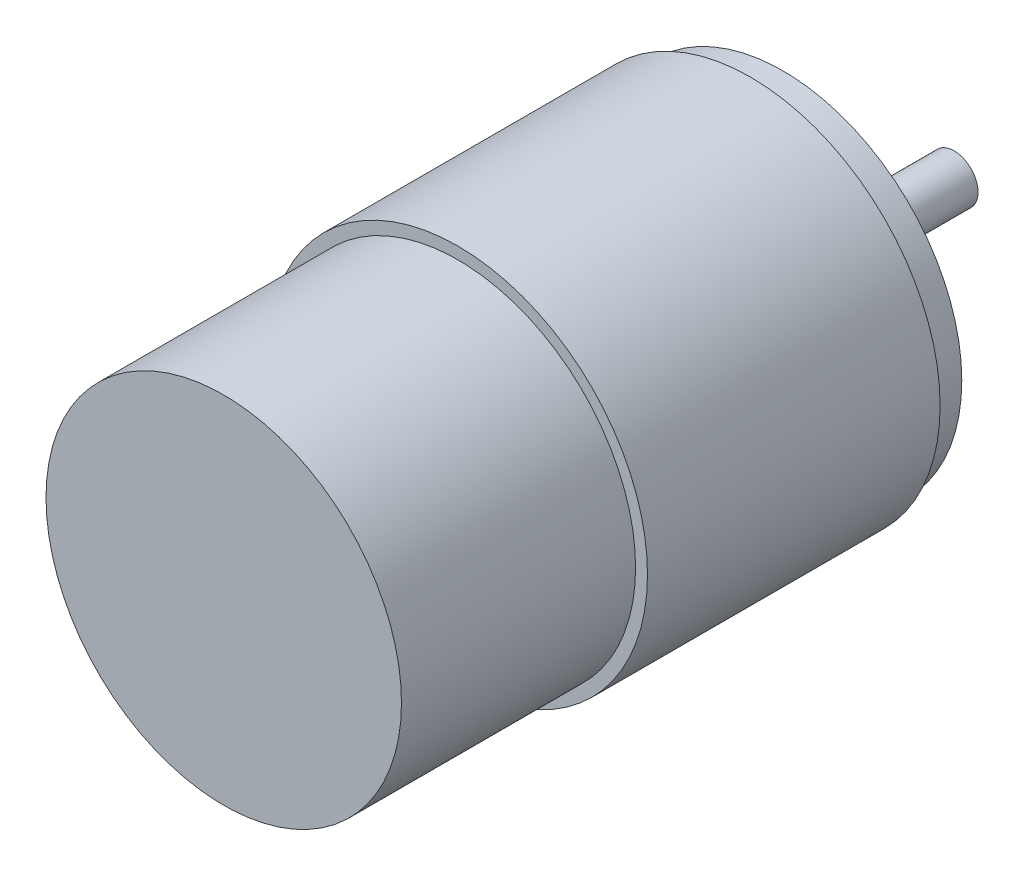
SolidWorks part; units mm, degrees
ref_plane "Front Plane" through (0, 0, 0) normal (0, 0, 1) x (1, 0, 0)
ref_plane "Top Plane" through (0, 0, 0) normal (0, 1, 0) x (1, 0, 0)
ref_plane "Right Plane" through (0, 0, 0) normal (1, 0, 0) x (0, 0, -1)
sketch "Sketch3" plane through (0, 0, 0) normal (0, 0, 1) x (1, 0, 0)
  circle A0 centre (0, 0) radius 20.955
  dimension "D1" = 41.91
extrude "Boss-Extrude3" add sketch "Sketch3" along normal blind 3.81
sketch "Sketch4" plane through (0, 0, 3.81) normal (0, 0, 1) x (1, 0, 0)
  circle A0 centre (0, 0) radius 22.225
  dimension "D1" = 44.45
extrude "Boss-Extrude4" add sketch "Sketch4" along normal blind 34.29
sketch "Sketch5" plane through (0, 0, 38.1) normal (0, 0, 1) x (1, 0, 0)
  circle A0 centre (0, 0) radius 20.828
  dimension "D1" = 41.656
extrude "Boss-Extrude5" add sketch "Sketch5" along normal blind 27.432
sketch "Sketch6" plane through (0, 0, 0) normal (0, 0, -1) x (-1, 0, 0)
  circle A0 centre (0, 0) radius 8.636
  dimension "D1" = 17.272
extrude "Boss-Extrude6" add sketch "Sketch6" along normal blind 4.064
sketch "Sketch7" plane through (0, 0, -4.064) normal (0, 0, -1) x (-1, 0, 0)
  circle A0 centre (0, 0) radius 2.794
  dimension "D1" = 5.588
extrude "Boss-Extrude7" add sketch "Sketch7" along normal blind 16.002
